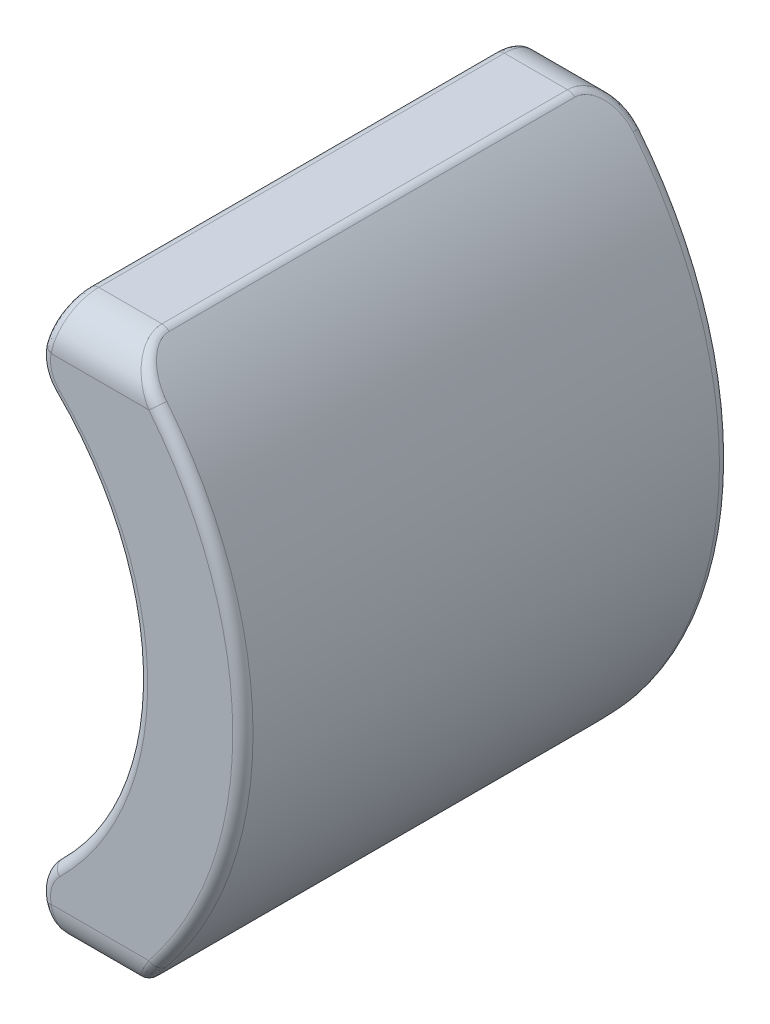
SolidWorks part; units mm, degrees
ref_plane "前视基准面" through (0, 0, 0) normal (0, 0, 1) x (1, 0, 0)
ref_plane "上视基准面" through (0, 0, 0) normal (0, 1, 0) x (1, 0, 0)
ref_plane "右视基准面" through (0, 0, 0) normal (1, 0, 0) x (0, 0, -1)
sketch "草图1" plane through (0, 0, 0) normal (0, 0, 1) x (1, 0, 0)
  line L0 (0, 0) -> (9.63, 0) construction
  line L1 (4.8781, -6.88) -> (4.5318, -5.38)
  line L2 (4.8781, -6.88) -> (6.7381, -6.88)
  line L3 (4.8781, 6.88) -> (6.7381, 6.88)
  line L4 (4.8781, 6.88) -> (4.5318, 5.38)
  arc A0 (6.7381, 6.88) -> (6.7381, -6.88) centre (0, 0) cw
  arc A3 (4.5318, 5.38) -> (4.5318, -5.38) centre (0, 0) cw
  point P0 (9.63, 0)
  dimension "D1" = 9.63
  dimension "D2" = 6.88
  dimension "D3" = 103
  dimension "D4" = 1.86
  dimension "D5" = 1.5
sketch "草图2" plane through (0, 0, 0) normal (0, 0, 1) x (1, 0, 0)
extrude "凸台-拉伸1" add sketch "草图1" along normal blind 12
fillet "圆角1" radius 1 2 edges at (4.5318, -5.38, 6) (4.5318, 5.38, 6)
fillet "圆角2" radius 1 4 edges at (5.8081, -6.88, 12) (5.8081, -6.88, 0) (5.8081, 6.88, 0) (5.8081, 6.88, 12)
fillet "圆角3" radius 0.25 24 edges at (4.8161, -6.6112, 11.6822) (4.6879, -5.4113, 12) (7.0343, 0, 12) (4.6879, 5.4113, 12) (4.8161, 6.6112, 11.6822) (4.8781, 6.88, 6) (4.8161, 6.6112, 0.3178) (4.6879, 5.4113, 0) (7.0343, 0, 0) (4.6879, -5.4113, 0) (4.8161, -6.6112, 0.3178) (6.9882, -6.6258, 11.6661) (9.63, 0, 12) (6.8685, 6.7498, 11.4934) (6.7381, 6.88, 6) (6.9882, 6.6258, 0.3339) (9.63, 0, 0) (6.8685, -6.7498, 0.5066) (4.8781, -6.88, 6) (6.7381, -6.88, 6)
